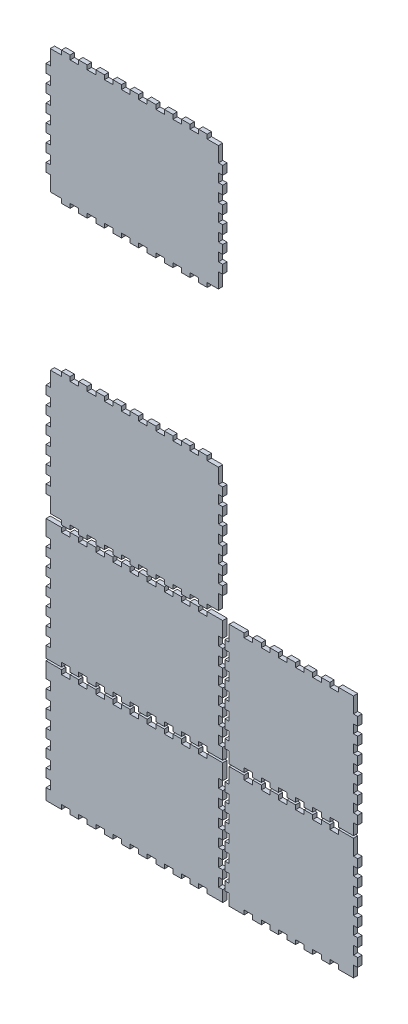
SolidWorks part; units mm, degrees
material "Maple"
ref_plane "Front Plane" through (0, 0, 0) normal (0, 0, 1) x (1, 0, 0)
ref_plane "Top Plane" through (0, 0, 0) normal (0, 1, 0) x (1, 0, 0)
ref_plane "Right Plane" through (0, 0, 0) normal (1, 0, 0) x (0, 0, -1)
sketch "Model" plane through (0, 0, 0) normal (0, 0, 1) x (1, 0, 0)
  line L4 (13.9995, 22.0004) -> (24.5001, 22.0004)
  line L5 (24.5001, 22.0004) -> (24.5001, 25.9994)
  line L6 (24.5001, 25.9994) -> (32.4997, 25.9994)
  line L7 (32.4997, 25.9994) -> (32.4997, 22.0004)
  line L8 (32.4997, 22.0004) -> (40.5007, 22.0004)
  line L9 (40.5007, 22.0004) -> (40.5007, 25.9994)
  line L10 (40.5007, 25.9994) -> (48.4999, 25.9994)
  line L11 (48.4999, 25.9994) -> (48.4999, 22.0004)
  line L12 (48.4999, 22.0004) -> (56.4995, 22.0004)
  line L13 (56.4995, 22.0004) -> (56.4995, 25.9994)
  line L14 (56.4995, 25.9994) -> (64.5005, 25.9994)
  line L15 (64.5005, 25.9994) -> (64.5005, 22.0004)
  line L16 (64.5005, 22.0004) -> (72.5001, 22.0004)
  line L17 (72.5001, 22.0004) -> (72.5001, 25.9994)
  line L18 (72.5001, 25.9994) -> (80.4997, 25.9994)
  line L19 (80.4997, 25.9994) -> (80.4997, 22.0004)
  line L20 (80.4997, 22.0004) -> (88.5003, 22.0004)
  line L21 (88.5003, 22.0004) -> (88.5003, 25.9994)
  line L22 (88.5003, 25.9994) -> (96.4999, 25.9994)
  line L23 (96.4999, 25.9994) -> (96.4999, 22.0004)
  line L24 (96.4999, 22.0004) -> (104.499, 22.0004)
  line L25 (104.499, 22.0004) -> (104.499, 25.9994)
  line L26 (104.499, 25.9994) -> (112.5, 25.9994)
  line L27 (112.5, 25.9994) -> (112.5, 22.0004)
  line L28 (112.5, 22.0004) -> (120.5, 22.0004)
  line L29 (120.5, 22.0004) -> (120.5, 25.9994)
  line L30 (120.5, 25.9994) -> (128.501, 25.9994)
  line L31 (128.501, 25.9994) -> (128.501, 22.0004)
  line L32 (128.501, 22.0004) -> (136.5, 22.0004)
  line L33 (136.5, 22.0004) -> (136.5, 25.9994)
  line L34 (136.5, 25.9994) -> (144.5, 25.9994)
  line L35 (144.5, 25.9994) -> (144.5, 22.0004)
  line L36 (144.5, 22.0004) -> (152.499, 22.0004)
  line L37 (152.499, 22.0004) -> (152.499, 25.9994)
  line L38 (152.499, 25.9994) -> (160.5, 25.9994)
  line L39 (160.5, 25.9994) -> (160.5, 22.0004)
  line L40 (160.5, 22.0004) -> (171, 22.0004)
  line L41 (171, 22.0004) -> (175, 22.0004)
  line L42 (175, 22.0004) -> (175, 32.4997)
  line L43 (175, 32.4997) -> (171, 32.4997)
  line L44 (171, 32.4997) -> (171, 40.5007)
  line L45 (171, 40.5007) -> (175, 40.5007)
  line L46 (175, 40.5007) -> (175, 48.4999)
  line L47 (175, 48.4999) -> (171, 48.4999)
  line L48 (171, 48.4999) -> (171, 56.4995)
  line L49 (171, 56.4995) -> (175, 56.4995)
  line L50 (175, 56.4995) -> (175, 64.5005)
  line L51 (175, 64.5005) -> (171, 64.5005)
  line L52 (171, 64.5005) -> (171, 72.5001)
  line L53 (171, 72.5001) -> (175, 72.5001)
  line L54 (175, 72.5001) -> (175, 80.4997)
  line L55 (175, 80.4997) -> (171, 80.4997)
  line L56 (171, 80.4997) -> (171, 88.5003)
  line L57 (171, 88.5003) -> (175, 88.5003)
  line L58 (175, 88.5003) -> (175, 96.4999)
  line L59 (175, 96.4999) -> (171, 96.4999)
  line L60 (171, 96.4999) -> (171, 104.499)
  line L61 (171, 104.499) -> (175, 104.499)
  line L62 (175, 104.499) -> (175, 112.5)
  line L63 (175, 112.5) -> (171, 112.5)
  line L64 (171, 112.5) -> (171, 120.5)
  line L65 (171, 120.5) -> (175, 120.5)
  line L66 (175, 120.5) -> (175, 131)
  line L67 (175, 131) -> (175, 135)
  line L68 (175, 135) -> (171, 135)
  line L69 (171, 135) -> (160.5, 135)
  line L70 (160.5, 135) -> (160.5, 131)
  line L71 (160.5, 131) -> (152.499, 131)
  line L72 (152.499, 131) -> (152.499, 135)
  line L73 (152.499, 135) -> (144.5, 135)
  line L74 (144.5, 135) -> (144.5, 131)
  line L75 (144.5, 131) -> (136.5, 131)
  line L76 (136.5, 131) -> (136.5, 135)
  line L77 (136.5, 135) -> (128.501, 135)
  line L78 (128.501, 135) -> (128.501, 131)
  line L79 (128.501, 131) -> (120.5, 131)
  line L80 (120.5, 131) -> (120.5, 135)
  line L81 (120.5, 135) -> (112.5, 135)
  line L82 (112.5, 135) -> (112.5, 131)
  line L83 (112.5, 131) -> (104.499, 131)
  line L84 (104.499, 131) -> (104.499, 135)
  line L85 (104.499, 135) -> (96.4999, 135)
  line L86 (96.4999, 135) -> (96.4999, 131)
  line L87 (96.4999, 131) -> (88.5003, 131)
  line L88 (88.5003, 131) -> (88.5003, 135)
  line L89 (88.5003, 135) -> (80.4997, 135)
  line L90 (80.4997, 135) -> (80.4997, 131)
  line L91 (80.4997, 131) -> (72.5001, 131)
  line L92 (72.5001, 131) -> (72.5001, 135)
  line L93 (72.5001, 135) -> (64.5005, 135)
  line L94 (64.5005, 135) -> (64.5005, 131)
  line L95 (64.5005, 131) -> (56.4995, 131)
  line L96 (56.4995, 131) -> (56.4995, 135)
  line L97 (56.4995, 135) -> (48.4999, 135)
  line L98 (48.4999, 135) -> (48.4999, 131)
  line L99 (48.4999, 131) -> (40.5007, 131)
  line L100 (40.5007, 131) -> (40.5007, 135)
  line L101 (40.5007, 135) -> (32.4997, 135)
  line L102 (32.4997, 135) -> (32.4997, 131)
  line L103 (32.4997, 131) -> (24.5001, 131)
  line L104 (24.5001, 131) -> (24.5001, 135)
  line L105 (24.5001, 135) -> (13.9995, 135)
  line L106 (13.9995, 135) -> (10.0004, 135)
  line L107 (10.0004, 135) -> (10.0004, 131)
  line L108 (10.0004, 131) -> (10.0004, 120.5)
  line L109 (10.0004, 120.5) -> (13.9995, 120.5)
  line L110 (13.9995, 120.5) -> (13.9995, 112.5)
  line L111 (13.9995, 112.5) -> (10.0004, 112.5)
  line L112 (10.0004, 112.5) -> (10.0004, 104.499)
  line L113 (10.0004, 104.499) -> (13.9995, 104.499)
  line L114 (13.9995, 104.499) -> (13.9995, 96.4999)
  line L115 (13.9995, 96.4999) -> (10.0004, 96.4999)
  line L116 (10.0004, 96.4999) -> (10.0004, 88.5003)
  line L117 (10.0004, 88.5003) -> (13.9995, 88.5003)
  line L118 (13.9995, 88.5003) -> (13.9995, 80.4997)
  line L119 (13.9995, 80.4997) -> (10.0004, 80.4997)
  line L120 (10.0004, 80.4997) -> (10.0004, 72.5001)
  line L121 (10.0004, 72.5001) -> (13.9995, 72.5001)
  line L122 (13.9995, 72.5001) -> (13.9995, 64.5005)
  line L123 (13.9995, 64.5005) -> (10.0004, 64.5005)
  line L124 (10.0004, 64.5005) -> (10.0004, 56.4995)
  line L125 (10.0004, 56.4995) -> (13.9995, 56.4995)
  line L126 (13.9995, 56.4995) -> (13.9995, 48.4999)
  line L127 (13.9995, 48.4999) -> (10.0004, 48.4999)
  line L128 (10.0004, 48.4999) -> (10.0004, 40.5007)
  line L129 (10.0004, 40.5007) -> (13.9995, 40.5007)
  line L130 (13.9995, 40.5007) -> (13.9995, 32.4997)
  line L131 (13.9995, 32.4997) -> (10.0004, 32.4997)
  line L132 (10.0004, 32.4997) -> (10.0004, 22.0004)
  line L133 (10.0004, 22.0004) -> (13.9995, 22.0004)
  line L134 (13.9995, 137.001) -> (24.5001, 137.001)
  line L135 (24.5001, 137.001) -> (24.5001, 141)
  line L136 (24.5001, 141) -> (32.4997, 141)
  line L137 (32.4997, 141) -> (32.4997, 137.001)
  line L138 (32.4997, 137.001) -> (40.5007, 137.001)
  line L139 (40.5007, 137.001) -> (40.5007, 141)
  line L140 (40.5007, 141) -> (48.4999, 141)
  line L141 (48.4999, 141) -> (48.4999, 137.001)
  line L142 (48.4999, 137.001) -> (56.4995, 137.001)
  line L143 (56.4995, 137.001) -> (56.4995, 141)
  line L144 (56.4995, 141) -> (64.5005, 141)
  line L145 (64.5005, 141) -> (64.5005, 137.001)
  line L146 (64.5005, 137.001) -> (72.5001, 137.001)
  line L147 (72.5001, 137.001) -> (72.5001, 141)
  line L148 (72.5001, 141) -> (80.4997, 141)
  line L149 (80.4997, 141) -> (80.4997, 137.001)
  line L150 (80.4997, 137.001) -> (88.5003, 137.001)
  line L151 (88.5003, 137.001) -> (88.5003, 141)
  line L152 (88.5003, 141) -> (96.4999, 141)
  line L153 (96.4999, 141) -> (96.4999, 137.001)
  line L154 (96.4999, 137.001) -> (104.499, 137.001)
  line L155 (104.499, 137.001) -> (104.499, 141)
  line L156 (104.499, 141) -> (112.5, 141)
  line L157 (112.5, 141) -> (112.5, 137.001)
  line L158 (112.5, 137.001) -> (120.5, 137.001)
  line L159 (120.5, 137.001) -> (120.5, 141)
  line L160 (120.5, 141) -> (128.501, 141)
  line L161 (128.501, 141) -> (128.501, 137.001)
  line L162 (128.501, 137.001) -> (136.5, 137.001)
  line L163 (136.5, 137.001) -> (136.5, 141)
  line L164 (136.5, 141) -> (144.5, 141)
  line L165 (144.5, 141) -> (144.5, 137.001)
  line L166 (144.5, 137.001) -> (152.499, 137.001)
  line L167 (152.499, 137.001) -> (152.499, 141)
  line L168 (152.499, 141) -> (160.5, 141)
  line L169 (160.5, 141) -> (160.5, 137.001)
  line L170 (160.5, 137.001) -> (171, 137.001)
  line L171 (171, 137.001) -> (175, 137.001)
  line L172 (175, 137.001) -> (175, 147.5)
  line L173 (175, 147.5) -> (171, 147.5)
  line L174 (171, 147.5) -> (171, 155.499)
  line L175 (171, 155.499) -> (175, 155.499)
  line L176 (175, 155.499) -> (175, 163.5)
  line L177 (175, 163.5) -> (171, 163.5)
  line L178 (171, 163.5) -> (171, 171.5)
  line L179 (171, 171.5) -> (175, 171.5)
  line L180 (175, 171.5) -> (175, 179.5)
  line L181 (175, 179.5) -> (171, 179.5)
  line L182 (171, 179.5) -> (171, 187.5)
  line L183 (171, 187.5) -> (175, 187.5)
  line L184 (175, 187.5) -> (175, 195.5)
  line L185 (175, 195.5) -> (171, 195.5)
  line L186 (171, 195.5) -> (171, 203.501)
  line L187 (171, 203.501) -> (175, 203.501)
  line L188 (175, 203.501) -> (175, 211.5)
  line L189 (175, 211.5) -> (171, 211.5)
  line L190 (171, 211.5) -> (171, 219.499)
  line L191 (171, 219.499) -> (175, 219.499)
  line L192 (175, 219.499) -> (175, 227.5)
  line L193 (175, 227.5) -> (171, 227.5)
  line L194 (171, 227.5) -> (171, 235.5)
  line L195 (171, 235.5) -> (175, 235.5)
  line L196 (175, 235.5) -> (175, 246)
  line L197 (175, 246) -> (175, 249.999)
  line L198 (175, 249.999) -> (171, 249.999)
  line L199 (171, 249.999) -> (160.5, 249.999)
  line L200 (160.5, 249.999) -> (160.5, 246)
  line L201 (160.5, 246) -> (152.499, 246)
  line L202 (152.499, 246) -> (152.499, 249.999)
  line L203 (152.499, 249.999) -> (144.5, 249.999)
  line L204 (144.5, 249.999) -> (144.5, 246)
  line L205 (144.5, 246) -> (136.5, 246)
  line L206 (136.5, 246) -> (136.5, 249.999)
  line L207 (136.5, 249.999) -> (128.501, 249.999)
  line L208 (128.501, 249.999) -> (128.501, 246)
  line L209 (128.501, 246) -> (120.5, 246)
  line L210 (120.5, 246) -> (120.5, 249.999)
  line L211 (120.5, 249.999) -> (112.5, 249.999)
  line L212 (112.5, 249.999) -> (112.5, 246)
  line L213 (112.5, 246) -> (104.499, 246)
  line L214 (104.499, 246) -> (104.499, 249.999)
  line L215 (104.499, 249.999) -> (96.4999, 249.999)
  line L216 (96.4999, 249.999) -> (96.4999, 246)
  line L217 (96.4999, 246) -> (88.5003, 246)
  line L218 (88.5003, 246) -> (88.5003, 249.999)
  line L219 (88.5003, 249.999) -> (80.4997, 249.999)
  line L220 (80.4997, 249.999) -> (80.4997, 246)
  line L221 (80.4997, 246) -> (72.5001, 246)
  line L222 (72.5001, 246) -> (72.5001, 249.999)
  line L223 (72.5001, 249.999) -> (64.5005, 249.999)
  line L224 (64.5005, 249.999) -> (64.5005, 246)
  line L225 (64.5005, 246) -> (56.4995, 246)
  line L226 (56.4995, 246) -> (56.4995, 249.999)
  line L227 (56.4995, 249.999) -> (48.4999, 249.999)
  line L228 (48.4999, 249.999) -> (48.4999, 246)
  line L229 (48.4999, 246) -> (40.5007, 246)
  line L230 (40.5007, 246) -> (40.5007, 249.999)
  line L231 (40.5007, 249.999) -> (32.4997, 249.999)
  line L232 (32.4997, 249.999) -> (32.4997, 246)
  line L233 (32.4997, 246) -> (24.5001, 246)
  line L234 (24.5001, 246) -> (24.5001, 249.999)
  line L235 (24.5001, 249.999) -> (13.9995, 249.999)
  line L236 (13.9995, 249.999) -> (10.0004, 249.999)
  line L237 (10.0004, 249.999) -> (10.0004, 246)
  line L238 (10.0004, 246) -> (10.0004, 235.5)
  line L239 (10.0004, 235.5) -> (13.9995, 235.5)
  line L240 (13.9995, 235.5) -> (13.9995, 227.5)
  line L241 (13.9995, 227.5) -> (10.0004, 227.5)
  line L242 (10.0004, 227.5) -> (10.0004, 219.499)
  line L243 (10.0004, 219.499) -> (13.9995, 219.499)
  line L244 (13.9995, 219.499) -> (13.9995, 211.5)
  line L245 (13.9995, 211.5) -> (10.0004, 211.5)
  line L246 (10.0004, 211.5) -> (10.0004, 203.501)
  line L247 (10.0004, 203.501) -> (13.9995, 203.501)
  line L248 (13.9995, 203.501) -> (13.9995, 195.5)
  line L249 (13.9995, 195.5) -> (10.0004, 195.5)
  line L250 (10.0004, 195.5) -> (10.0004, 187.5)
  line L251 (10.0004, 187.5) -> (13.9995, 187.5)
  line L252 (13.9995, 187.5) -> (13.9995, 179.5)
  line L253 (13.9995, 179.5) -> (10.0004, 179.5)
  line L254 (10.0004, 179.5) -> (10.0004, 171.5)
  line L255 (10.0004, 171.5) -> (13.9995, 171.5)
  line L256 (13.9995, 171.5) -> (13.9995, 163.5)
  line L257 (13.9995, 163.5) -> (10.0004, 163.5)
  line L258 (10.0004, 163.5) -> (10.0004, 155.499)
  line L259 (10.0004, 155.499) -> (13.9995, 155.499)
  line L260 (13.9995, 155.499) -> (13.9995, 147.5)
  line L261 (13.9995, 147.5) -> (10.0004, 147.5)
  line L262 (10.0004, 147.5) -> (10.0004, 137.001)
  line L263 (10.0004, 137.001) -> (13.9995, 137.001)
  line L264 (13.9995, 256) -> (24.5001, 256)
  line L265 (24.5001, 256) -> (24.5001, 252)
  line L266 (24.5001, 252) -> (32.4997, 252)
  line L267 (32.4997, 252) -> (32.4997, 256)
  line L268 (32.4997, 256) -> (40.5007, 256)
  line L269 (40.5007, 256) -> (40.5007, 252)
  line L270 (40.5007, 252) -> (48.4999, 252)
  line L271 (48.4999, 252) -> (48.4999, 256)
  line L272 (48.4999, 256) -> (56.4995, 256)
  line L273 (56.4995, 256) -> (56.4995, 252)
  line L274 (56.4995, 252) -> (64.5005, 252)
  line L275 (64.5005, 252) -> (64.5005, 256)
  line L276 (64.5005, 256) -> (72.5001, 256)
  line L277 (72.5001, 256) -> (72.5001, 252)
  line L278 (72.5001, 252) -> (80.4997, 252)
  line L279 (80.4997, 252) -> (80.4997, 256)
  line L280 (80.4997, 256) -> (88.5003, 256)
  line L281 (88.5003, 256) -> (88.5003, 252)
  line L282 (88.5003, 252) -> (96.4999, 252)
  line L283 (96.4999, 252) -> (96.4999, 256)
  line L284 (96.4999, 256) -> (104.499, 256)
  line L285 (104.499, 256) -> (104.499, 252)
  line L286 (104.499, 252) -> (112.5, 252)
  line L287 (112.5, 252) -> (112.5, 256)
  line L288 (112.5, 256) -> (120.5, 256)
  line L289 (120.5, 256) -> (120.5, 252)
  line L290 (120.5, 252) -> (128.501, 252)
  line L291 (128.501, 252) -> (128.501, 256)
  line L292 (128.501, 256) -> (136.5, 256)
  line L293 (136.5, 256) -> (136.5, 252)
  line L294 (136.5, 252) -> (144.5, 252)
  line L295 (144.5, 252) -> (144.5, 256)
  line L296 (144.5, 256) -> (152.499, 256)
  line L297 (152.499, 256) -> (152.499, 252)
  line L298 (152.499, 252) -> (160.5, 252)
  line L299 (160.5, 252) -> (160.5, 256)
  line L300 (160.5, 256) -> (171, 256)
  line L301 (171, 256) -> (171, 270)
  line L302 (171, 270) -> (175, 270)
  line L303 (175, 270) -> (175, 278)
  line L304 (175, 278) -> (171, 278)
  line L305 (171, 278) -> (171, 285.999)
  line L306 (171, 285.999) -> (175, 285.999)
  line L307 (175, 285.999) -> (175, 294)
  line L308 (175, 294) -> (171, 294)
  line L309 (171, 294) -> (171, 302)
  line L310 (171, 302) -> (175, 302)
  line L311 (175, 302) -> (175, 309.999)
  line L312 (175, 309.999) -> (171, 309.999)
  line L313 (171, 309.999) -> (171, 318)
  line L314 (171, 318) -> (175, 318)
  line L315 (175, 318) -> (175, 326)
  line L316 (175, 326) -> (171, 326)
  line L317 (171, 326) -> (171, 334)
  line L318 (171, 334) -> (175, 334)
  line L319 (175, 334) -> (175, 342)
  line L320 (175, 342) -> (171, 342)
  line L321 (171, 342) -> (171, 350)
  line L322 (171, 350) -> (175, 350)
  line L323 (175, 350) -> (175, 357.999)
  line L324 (175, 357.999) -> (171, 357.999)
  line L325 (171, 357.999) -> (171, 372.001)
  line L326 (171, 372.001) -> (160.5, 372.001)
  line L327 (160.5, 372.001) -> (160.5, 376.001)
  line L328 (160.5, 376.001) -> (152.499, 376.001)
  line L329 (152.499, 376.001) -> (152.499, 372.001)
  line L330 (152.499, 372.001) -> (144.5, 372.001)
  line L331 (144.5, 372.001) -> (144.5, 376.001)
  line L332 (144.5, 376.001) -> (136.5, 376.001)
  line L333 (136.5, 376.001) -> (136.5, 372.001)
  line L334 (136.5, 372.001) -> (128.501, 372.001)
  line L335 (128.501, 372.001) -> (128.501, 376.001)
  line L336 (128.501, 376.001) -> (120.5, 376.001)
  line L337 (120.5, 376.001) -> (120.5, 372.001)
  line L338 (120.5, 372.001) -> (112.5, 372.001)
  line L339 (112.5, 372.001) -> (112.5, 376.001)
  line L340 (112.5, 376.001) -> (104.499, 376.001)
  line L341 (104.499, 376.001) -> (104.499, 372.001)
  line L342 (104.499, 372.001) -> (96.4999, 372.001)
  line L343 (96.4999, 372.001) -> (96.4999, 376.001)
  line L344 (96.4999, 376.001) -> (88.5003, 376.001)
  line L345 (88.5003, 376.001) -> (88.5003, 372.001)
  line L346 (88.5003, 372.001) -> (80.4997, 372.001)
  line L347 (80.4997, 372.001) -> (80.4997, 376.001)
  line L348 (80.4997, 376.001) -> (72.5001, 376.001)
  line L349 (72.5001, 376.001) -> (72.5001, 372.001)
  line L350 (72.5001, 372.001) -> (64.5005, 372.001)
  line L351 (64.5005, 372.001) -> (64.5005, 376.001)
  line L352 (64.5005, 376.001) -> (56.4995, 376.001)
  line L353 (56.4995, 376.001) -> (56.4995, 372.001)
  line L354 (56.4995, 372.001) -> (48.4999, 372.001)
  line L355 (48.4999, 372.001) -> (48.4999, 376.001)
  line L356 (48.4999, 376.001) -> (40.5007, 376.001)
  line L357 (40.5007, 376.001) -> (40.5007, 372.001)
  line L358 (40.5007, 372.001) -> (32.4997, 372.001)
  line L359 (32.4997, 372.001) -> (32.4997, 376.001)
  line L360 (32.4997, 376.001) -> (24.5001, 376.001)
  line L361 (24.5001, 376.001) -> (24.5001, 372.001)
  line L362 (24.5001, 372.001) -> (13.9995, 372.001)
  line L363 (13.9995, 372.001) -> (13.9995, 357.999)
  line L364 (13.9995, 357.999) -> (10.0004, 357.999)
  line L365 (10.0004, 357.999) -> (10.0004, 350)
  line L366 (10.0004, 350) -> (13.9995, 350)
  line L367 (13.9995, 350) -> (13.9995, 342)
  line L368 (13.9995, 342) -> (10.0004, 342)
  line L369 (10.0004, 342) -> (10.0004, 334)
  line L370 (10.0004, 334) -> (13.9995, 334)
  line L371 (13.9995, 334) -> (13.9995, 326)
  line L372 (13.9995, 326) -> (10.0004, 326)
  line L373 (10.0004, 326) -> (10.0004, 318)
  line L374 (10.0004, 318) -> (13.9995, 318)
  line L375 (13.9995, 318) -> (13.9995, 309.999)
  line L376 (13.9995, 309.999) -> (10.0004, 309.999)
  line L377 (10.0004, 309.999) -> (10.0004, 302)
  line L378 (10.0004, 302) -> (13.9995, 302)
  line L379 (13.9995, 302) -> (13.9995, 294)
  line L380 (13.9995, 294) -> (10.0004, 294)
  line L381 (10.0004, 294) -> (10.0004, 285.999)
  line L382 (10.0004, 285.999) -> (13.9995, 285.999)
  line L383 (13.9995, 285.999) -> (13.9995, 278)
  line L384 (13.9995, 278) -> (10.0004, 278)
  line L385 (10.0004, 278) -> (10.0004, 270)
  line L386 (10.0004, 270) -> (13.9995, 270)
  line L387 (13.9995, 270) -> (13.9995, 256)
  line L388 (13.9995, 516.001) -> (24.5001, 516.001)
  line L389 (24.5001, 516.001) -> (24.5001, 512)
  line L390 (24.5001, 512) -> (32.4997, 512)
  line L391 (32.4997, 512) -> (32.4997, 516.001)
  line L392 (32.4997, 516.001) -> (40.5007, 516.001)
  line L393 (40.5007, 516.001) -> (40.5007, 512)
  line L394 (40.5007, 512) -> (48.4999, 512)
  line L395 (48.4999, 512) -> (48.4999, 516.001)
  line L396 (48.4999, 516.001) -> (56.4995, 516.001)
  line L397 (56.4995, 516.001) -> (56.4995, 512)
  line L398 (56.4995, 512) -> (64.5005, 512)
  line L399 (64.5005, 512) -> (64.5005, 516.001)
  line L400 (64.5005, 516.001) -> (72.5001, 516.001)
  line L401 (72.5001, 516.001) -> (72.5001, 512)
  line L402 (72.5001, 512) -> (80.4997, 512)
  line L403 (80.4997, 512) -> (80.4997, 516.001)
  line L404 (80.4997, 516.001) -> (88.5003, 516.001)
  line L405 (88.5003, 516.001) -> (88.5003, 512)
  line L406 (88.5003, 512) -> (96.4999, 512)
  line L407 (96.4999, 512) -> (96.4999, 516.001)
  line L408 (96.4999, 516.001) -> (104.499, 516.001)
  line L409 (104.499, 516.001) -> (104.499, 512)
  line L410 (104.499, 512) -> (112.5, 512)
  line L411 (112.5, 512) -> (112.5, 516.001)
  line L412 (112.5, 516.001) -> (120.5, 516.001)
  line L413 (120.5, 516.001) -> (120.5, 512)
  line L414 (120.5, 512) -> (128.501, 512)
  line L415 (128.501, 512) -> (128.501, 516.001)
  line L416 (128.501, 516.001) -> (136.5, 516.001)
  line L417 (136.5, 516.001) -> (136.5, 512)
  line L418 (136.5, 512) -> (144.5, 512)
  line L419 (144.5, 512) -> (144.5, 516.001)
  line L420 (144.5, 516.001) -> (152.499, 516.001)
  line L421 (152.499, 516.001) -> (152.499, 512)
  line L422 (152.499, 512) -> (160.5, 512)
  line L423 (160.5, 512) -> (160.5, 516.001)
  line L424 (160.5, 516.001) -> (171, 516.001)
  line L425 (171, 516.001) -> (171, 529.999)
  line L426 (171, 529.999) -> (175, 529.999)
  line L427 (175, 529.999) -> (175, 538)
  line L428 (175, 538) -> (171, 538)
  line L429 (171, 538) -> (171, 546.001)
  line L430 (171, 546.001) -> (175, 546.001)
  line L431 (175, 546.001) -> (175, 553.999)
  line L432 (175, 553.999) -> (171, 553.999)
  line L433 (171, 553.999) -> (171, 562)
  line L434 (171, 562) -> (175, 562)
  line L435 (175, 562) -> (175, 570.001)
  line L436 (175, 570.001) -> (171, 570.001)
  line L437 (171, 570.001) -> (171, 578.002)
  line L438 (171, 578.002) -> (175, 578.002)
  line L439 (175, 578.002) -> (175, 585.999)
  line L440 (175, 585.999) -> (171, 585.999)
  line L441 (171, 585.999) -> (171, 594)
  line L442 (171, 594) -> (175, 594)
  line L443 (175, 594) -> (175, 602.001)
  line L444 (175, 602.001) -> (171, 602.001)
  line L445 (171, 602.001) -> (171, 609.999)
  line L446 (171, 609.999) -> (175, 609.999)
  line L447 (175, 609.999) -> (175, 618)
  line L448 (175, 618) -> (171, 618)
  line L449 (171, 618) -> (171, 632.001)
  line L450 (171, 632.001) -> (160.5, 632.001)
  line L451 (160.5, 632.001) -> (160.5, 636.002)
  line L452 (160.5, 636.002) -> (152.499, 636.002)
  line L453 (152.499, 636.002) -> (152.499, 632.001)
  line L454 (152.499, 632.001) -> (144.5, 632.001)
  line L455 (144.5, 632.001) -> (144.5, 636.002)
  line L456 (144.5, 636.002) -> (136.5, 636.002)
  line L457 (136.5, 636.002) -> (136.5, 632.001)
  line L458 (136.5, 632.001) -> (128.501, 632.001)
  line L459 (128.501, 632.001) -> (128.501, 636.002)
  line L460 (128.501, 636.002) -> (120.5, 636.002)
  line L461 (120.5, 636.002) -> (120.5, 632.001)
  line L462 (120.5, 632.001) -> (112.5, 632.001)
  line L463 (112.5, 632.001) -> (112.5, 636.002)
  line L464 (112.5, 636.002) -> (104.499, 636.002)
  line L465 (104.499, 636.002) -> (104.499, 632.001)
  line L466 (104.499, 632.001) -> (96.4999, 632.001)
  line L467 (96.4999, 632.001) -> (96.4999, 636.002)
  line L468 (96.4999, 636.002) -> (88.5003, 636.002)
  line L469 (88.5003, 636.002) -> (88.5003, 632.001)
  line L470 (88.5003, 632.001) -> (80.4997, 632.001)
  line L471 (80.4997, 632.001) -> (80.4997, 636.002)
  line L472 (80.4997, 636.002) -> (72.5001, 636.002)
  line L473 (72.5001, 636.002) -> (72.5001, 632.001)
  line L474 (72.5001, 632.001) -> (64.5005, 632.001)
  line L475 (64.5005, 632.001) -> (64.5005, 636.002)
  line L476 (64.5005, 636.002) -> (56.4995, 636.002)
  line L477 (56.4995, 636.002) -> (56.4995, 632.001)
  line L478 (56.4995, 632.001) -> (48.4999, 632.001)
  line L479 (48.4999, 632.001) -> (48.4999, 636.002)
  line L480 (48.4999, 636.002) -> (40.5007, 636.002)
  line L481 (40.5007, 636.002) -> (40.5007, 632.001)
  line L482 (40.5007, 632.001) -> (32.4997, 632.001)
  line L483 (32.4997, 632.001) -> (32.4997, 636.002)
  line L484 (32.4997, 636.002) -> (24.5001, 636.002)
  line L485 (24.5001, 636.002) -> (24.5001, 632.001)
  line L486 (24.5001, 632.001) -> (13.9995, 632.001)
  line L487 (13.9995, 632.001) -> (13.9995, 618)
  line L488 (13.9995, 618) -> (10.0004, 618)
  line L489 (10.0004, 618) -> (10.0004, 609.999)
  line L490 (10.0004, 609.999) -> (13.9995, 609.999)
  line L491 (13.9995, 609.999) -> (13.9995, 602.001)
  line L492 (13.9995, 602.001) -> (10.0004, 602.001)
  line L493 (10.0004, 602.001) -> (10.0004, 594)
  line L494 (10.0004, 594) -> (13.9995, 594)
  line L495 (13.9995, 594) -> (13.9995, 585.999)
  line L496 (13.9995, 585.999) -> (10.0004, 585.999)
  line L497 (10.0004, 585.999) -> (10.0004, 578.002)
  line L498 (10.0004, 578.002) -> (13.9995, 578.002)
  line L499 (13.9995, 578.002) -> (13.9995, 570.001)
  line L500 (13.9995, 570.001) -> (10.0004, 570.001)
  line L501 (10.0004, 570.001) -> (10.0004, 562)
  line L502 (10.0004, 562) -> (13.9995, 562)
  line L503 (13.9995, 562) -> (13.9995, 553.999)
  line L504 (13.9995, 553.999) -> (10.0004, 553.999)
  line L505 (10.0004, 553.999) -> (10.0004, 546.001)
  line L506 (10.0004, 546.001) -> (13.9995, 546.001)
  line L507 (13.9995, 546.001) -> (13.9995, 538)
  line L508 (13.9995, 538) -> (10.0004, 538)
  line L509 (10.0004, 538) -> (10.0004, 529.999)
  line L510 (10.0004, 529.999) -> (13.9995, 529.999)
  line L511 (13.9995, 529.999) -> (13.9995, 516.001)
  line L512 (181, 22.0004) -> (195.001, 22.0004)
  line L513 (195.001, 22.0004) -> (195.001, 25.9994)
  line L514 (195.001, 25.9994) -> (203, 25.9994)
  line L515 (203, 25.9994) -> (203, 22.0004)
  line L516 (203, 22.0004) -> (211, 22.0004)
  line L517 (211, 22.0004) -> (211, 25.9994)
  line L518 (211, 25.9994) -> (218.999, 25.9994)
  line L519 (218.999, 25.9994) -> (218.999, 22.0004)
  line L520 (218.999, 22.0004) -> (227, 22.0004)
  line L521 (227, 22.0004) -> (227, 25.9994)
  line L522 (227, 25.9994) -> (235, 25.9994)
  line L523 (235, 25.9994) -> (235, 22.0004)
  line L524 (235, 22.0004) -> (243, 22.0004)
  line L525 (243, 22.0004) -> (243, 25.9994)
  line L526 (243, 25.9994) -> (251, 25.9994)
  line L527 (251, 25.9994) -> (251, 22.0004)
  line L528 (251, 22.0004) -> (259, 22.0004)
  line L529 (259, 22.0004) -> (259, 25.9994)
  line L530 (259, 25.9994) -> (267.001, 25.9994)
  line L531 (267.001, 25.9994) -> (267.001, 22.0004)
  line L532 (267.001, 22.0004) -> (275, 22.0004)
  line L533 (275, 22.0004) -> (275, 25.9994)
  line L534 (275, 25.9994) -> (282.999, 25.9994)
  line L535 (282.999, 25.9994) -> (282.999, 22.0004)
  line L536 (282.999, 22.0004) -> (297, 22.0004)
  line L537 (297, 22.0004) -> (297, 32.4997)
  line L538 (297, 32.4997) -> (301, 32.4997)
  line L539 (301, 32.4997) -> (301, 40.5007)
  line L540 (301, 40.5007) -> (297, 40.5007)
  line L541 (297, 40.5007) -> (297, 48.4999)
  line L542 (297, 48.4999) -> (301, 48.4999)
  line L543 (301, 48.4999) -> (301, 56.4995)
  line L544 (301, 56.4995) -> (297, 56.4995)
  line L545 (297, 56.4995) -> (297, 64.5005)
  line L546 (297, 64.5005) -> (301, 64.5005)
  line L547 (301, 64.5005) -> (301, 72.5001)
  line L548 (301, 72.5001) -> (297, 72.5001)
  line L549 (297, 72.5001) -> (297, 80.4997)
  line L550 (297, 80.4997) -> (301, 80.4997)
  line L551 (301, 80.4997) -> (301, 88.5003)
  line L552 (301, 88.5003) -> (297, 88.5003)
  line L553 (297, 88.5003) -> (297, 96.4999)
  line L554 (297, 96.4999) -> (301, 96.4999)
  line L555 (301, 96.4999) -> (301, 104.499)
  line L556 (301, 104.499) -> (297, 104.499)
  line L557 (297, 104.499) -> (297, 112.5)
  line L558 (297, 112.5) -> (301, 112.5)
  line L559 (301, 112.5) -> (301, 120.5)
  line L560 (301, 120.5) -> (297, 120.5)
  line L561 (297, 120.5) -> (297, 131)
  line L562 (297, 131) -> (297, 135)
  line L563 (297, 135) -> (282.999, 135)
  line L564 (282.999, 135) -> (282.999, 131)
  line L565 (282.999, 131) -> (275, 131)
  line L566 (275, 131) -> (275, 135)
  line L567 (275, 135) -> (267.001, 135)
  line L568 (267.001, 135) -> (267.001, 131)
  line L569 (267.001, 131) -> (259, 131)
  line L570 (259, 131) -> (259, 135)
  line L571 (259, 135) -> (251, 135)
  line L572 (251, 135) -> (251, 131)
  line L573 (251, 131) -> (243, 131)
  line L574 (243, 131) -> (243, 135)
  line L575 (243, 135) -> (235, 135)
  line L576 (235, 135) -> (235, 131)
  line L577 (235, 131) -> (227, 131)
  line L578 (227, 131) -> (227, 135)
  line L579 (227, 135) -> (218.999, 135)
  line L580 (218.999, 135) -> (218.999, 131)
  line L581 (218.999, 131) -> (211, 131)
  line L582 (211, 131) -> (211, 135)
  line L583 (211, 135) -> (203, 135)
  line L584 (203, 135) -> (203, 131)
  line L585 (203, 131) -> (195.001, 131)
  line L586 (195.001, 131) -> (195.001, 135)
  line L587 (195.001, 135) -> (181, 135)
  line L588 (181, 135) -> (181, 131)
  line L589 (181, 131) -> (181, 120.5)
  line L590 (181, 120.5) -> (176.999, 120.5)
  line L591 (176.999, 120.5) -> (176.999, 112.5)
  line L592 (176.999, 112.5) -> (181, 112.5)
  line L593 (181, 112.5) -> (181, 104.499)
  line L594 (181, 104.499) -> (176.999, 104.499)
  line L595 (176.999, 104.499) -> (176.999, 96.4999)
  line L596 (176.999, 96.4999) -> (181, 96.4999)
  line L597 (181, 96.4999) -> (181, 88.5003)
  line L598 (181, 88.5003) -> (176.999, 88.5003)
  line L599 (176.999, 88.5003) -> (176.999, 80.4997)
  line L600 (176.999, 80.4997) -> (181, 80.4997)
  line L601 (181, 80.4997) -> (181, 72.5001)
  line L602 (181, 72.5001) -> (176.999, 72.5001)
  line L603 (176.999, 72.5001) -> (176.999, 64.5005)
  line L604 (176.999, 64.5005) -> (181, 64.5005)
  line L605 (181, 64.5005) -> (181, 56.4995)
  line L606 (181, 56.4995) -> (176.999, 56.4995)
  line L607 (176.999, 56.4995) -> (176.999, 48.4999)
  line L608 (176.999, 48.4999) -> (181, 48.4999)
  line L609 (181, 48.4999) -> (181, 40.5007)
  line L610 (181, 40.5007) -> (176.999, 40.5007)
  line L611 (176.999, 40.5007) -> (176.999, 32.4997)
  line L612 (176.999, 32.4997) -> (181, 32.4997)
  line L613 (181, 32.4997) -> (181, 22.0004)
  line L614 (181, 137.001) -> (195.001, 137.001)
  line L615 (195.001, 137.001) -> (195.001, 141)
  line L616 (195.001, 141) -> (203, 141)
  line L617 (203, 141) -> (203, 137.001)
  line L618 (203, 137.001) -> (211, 137.001)
  line L619 (211, 137.001) -> (211, 141)
  line L620 (211, 141) -> (218.999, 141)
  line L621 (218.999, 141) -> (218.999, 137.001)
  line L622 (218.999, 137.001) -> (227, 137.001)
  line L623 (227, 137.001) -> (227, 141)
  line L624 (227, 141) -> (235, 141)
  line L625 (235, 141) -> (235, 137.001)
  line L626 (235, 137.001) -> (243, 137.001)
  line L627 (243, 137.001) -> (243, 141)
  line L628 (243, 141) -> (251, 141)
  line L629 (251, 141) -> (251, 137.001)
  line L630 (251, 137.001) -> (259, 137.001)
  line L631 (259, 137.001) -> (259, 141)
  line L632 (259, 141) -> (267.001, 141)
  line L633 (267.001, 141) -> (267.001, 137.001)
  line L634 (267.001, 137.001) -> (275, 137.001)
  line L635 (275, 137.001) -> (275, 141)
  line L636 (275, 141) -> (282.999, 141)
  line L637 (282.999, 141) -> (282.999, 137.001)
  line L638 (282.999, 137.001) -> (297, 137.001)
  line L639 (297, 137.001) -> (297, 147.5)
  line L640 (297, 147.5) -> (301, 147.5)
  line L641 (301, 147.5) -> (301, 155.499)
  line L642 (301, 155.499) -> (297, 155.499)
  line L643 (297, 155.499) -> (297, 163.5)
  line L644 (297, 163.5) -> (301, 163.5)
  line L645 (301, 163.5) -> (301, 171.5)
  line L646 (301, 171.5) -> (297, 171.5)
  line L647 (297, 171.5) -> (297, 179.5)
  line L648 (297, 179.5) -> (301, 179.5)
  line L649 (301, 179.5) -> (301, 187.5)
  line L650 (301, 187.5) -> (297, 187.5)
  line L651 (297, 187.5) -> (297, 195.5)
  line L652 (297, 195.5) -> (301, 195.5)
  line L653 (301, 195.5) -> (301, 203.501)
  line L654 (301, 203.501) -> (297, 203.501)
  line L655 (297, 203.501) -> (297, 211.5)
  line L656 (297, 211.5) -> (301, 211.5)
  line L657 (301, 211.5) -> (301, 219.499)
  line L658 (301, 219.499) -> (297, 219.499)
  line L659 (297, 219.499) -> (297, 227.5)
  line L660 (297, 227.5) -> (301, 227.5)
  line L661 (301, 227.5) -> (301, 235.5)
  line L662 (301, 235.5) -> (297, 235.5)
  line L663 (297, 235.5) -> (297, 246)
  line L664 (297, 246) -> (297, 249.999)
  line L665 (297, 249.999) -> (282.999, 249.999)
  line L666 (282.999, 249.999) -> (282.999, 246)
  line L667 (282.999, 246) -> (275, 246)
  line L668 (275, 246) -> (275, 249.999)
  line L669 (275, 249.999) -> (267.001, 249.999)
  line L670 (267.001, 249.999) -> (267.001, 246)
  line L671 (267.001, 246) -> (259, 246)
  line L672 (259, 246) -> (259, 249.999)
  line L673 (259, 249.999) -> (251, 249.999)
  line L674 (251, 249.999) -> (251, 246)
  line L675 (251, 246) -> (243, 246)
  line L676 (243, 246) -> (243, 249.999)
  line L677 (243, 249.999) -> (235, 249.999)
  line L678 (235, 249.999) -> (235, 246)
  line L679 (235, 246) -> (227, 246)
  line L680 (227, 246) -> (227, 249.999)
  line L681 (227, 249.999) -> (218.999, 249.999)
  line L682 (218.999, 249.999) -> (218.999, 246)
  line L683 (218.999, 246) -> (211, 246)
  line L684 (211, 246) -> (211, 249.999)
  line L685 (211, 249.999) -> (203, 249.999)
  line L686 (203, 249.999) -> (203, 246)
  line L687 (203, 246) -> (195.001, 246)
  line L688 (195.001, 246) -> (195.001, 249.999)
  line L689 (195.001, 249.999) -> (181, 249.999)
  line L690 (181, 249.999) -> (181, 246)
  line L691 (181, 246) -> (181, 235.5)
  line L692 (181, 235.5) -> (176.999, 235.5)
  line L693 (176.999, 235.5) -> (176.999, 227.5)
  line L694 (176.999, 227.5) -> (181, 227.5)
  line L695 (181, 227.5) -> (181, 219.499)
  line L696 (181, 219.499) -> (176.999, 219.499)
  line L697 (176.999, 219.499) -> (176.999, 211.5)
  line L698 (176.999, 211.5) -> (181, 211.5)
  line L699 (181, 211.5) -> (181, 203.501)
  line L700 (181, 203.501) -> (176.999, 203.501)
  line L701 (176.999, 203.501) -> (176.999, 195.5)
  line L702 (176.999, 195.5) -> (181, 195.5)
  line L703 (181, 195.5) -> (181, 187.5)
  line L704 (181, 187.5) -> (176.999, 187.5)
  line L705 (176.999, 187.5) -> (176.999, 179.5)
  line L706 (176.999, 179.5) -> (181, 179.5)
  line L707 (181, 179.5) -> (181, 171.5)
  line L708 (181, 171.5) -> (176.999, 171.5)
  line L709 (176.999, 171.5) -> (176.999, 163.5)
  line L710 (176.999, 163.5) -> (181, 163.5)
  line L711 (181, 163.5) -> (181, 155.499)
  line L712 (181, 155.499) -> (176.999, 155.499)
  line L713 (176.999, 155.499) -> (176.999, 147.5)
  line L714 (176.999, 147.5) -> (181, 147.5)
  line L715 (181, 147.5) -> (181, 137.001)
extrude "Přidat vysunutím1" add sketch "Model" along normal blind 4
other "Uložit těla1"
other "Uložit těla2"
